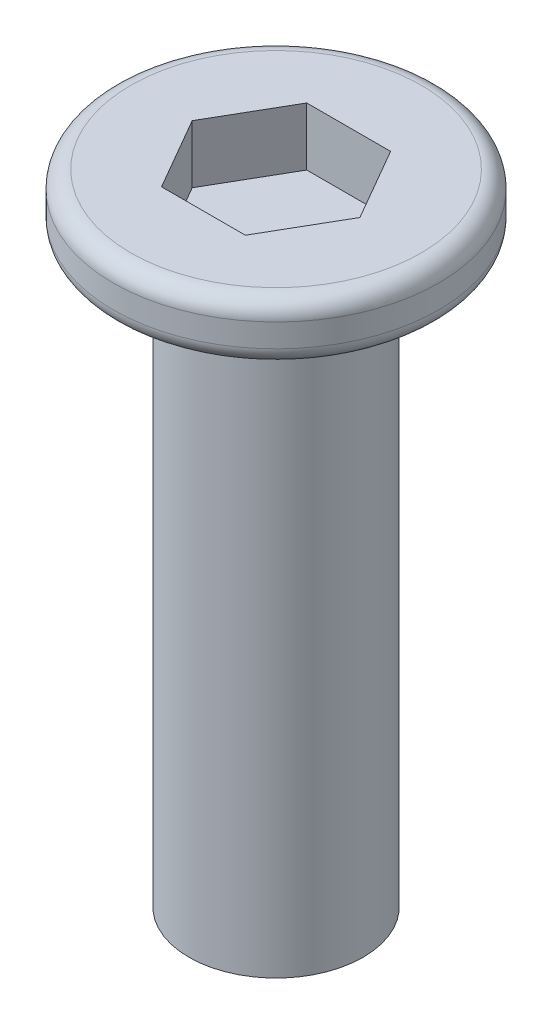
SolidWorks part; units mm, degrees
material "镀铬不锈钢"
ref_plane "前视基准面" through (0, 0, 0) normal (0, 0, 1) x (1, 0, 0)
ref_plane "上视基准面" through (0, 0, 0) normal (0, 1, 0) x (1, 0, 0)
ref_plane "右视基准面" through (0, 0, 0) normal (1, 0, 0) x (0, 0, -1)
other "Configuration Table"
sketch "草图1" plane through (0, 0, 0) normal (0, 1, 0) x (1, 0, 0)
  circle A0 centre (0, 0) radius 1.5
extrude "凸台-拉伸1" add sketch "草图1" along normal blind 10
sketch "草图2" plane through (0, 10, 0) normal (0, 1, 0) x (1, 0, 0)
  circle A0 centre (0, 0) radius 2.8
extrude "凸台-拉伸2" add sketch "草图2" along normal blind 1
sketch "草图3" plane through (0, 11, 0) normal (0, 1, 0) x (1, 0, 0)
  line L1 (-1.4434, 0) -> (-0.7217, -1.25)
  line L2 (-0.7217, -1.25) -> (0.7217, -1.25)
  line L3 (0.7217, -1.25) -> (1.4434, 0)
  line L4 (1.4434, 0) -> (0.7217, 1.25)
  line L5 (0.7217, 1.25) -> (-0.7217, 1.25)
  line L6 (-0.7217, 1.25) -> (-1.4434, 0)
  circle A0 centre (0, 0) radius 1.25 construction
extrude "切除-拉伸1" cut sketch "草图3" against normal blind 1
fillet "圆角1" radius 0.3 2 edges at (0, 10, 2.8) (0, 11, 2.8)
